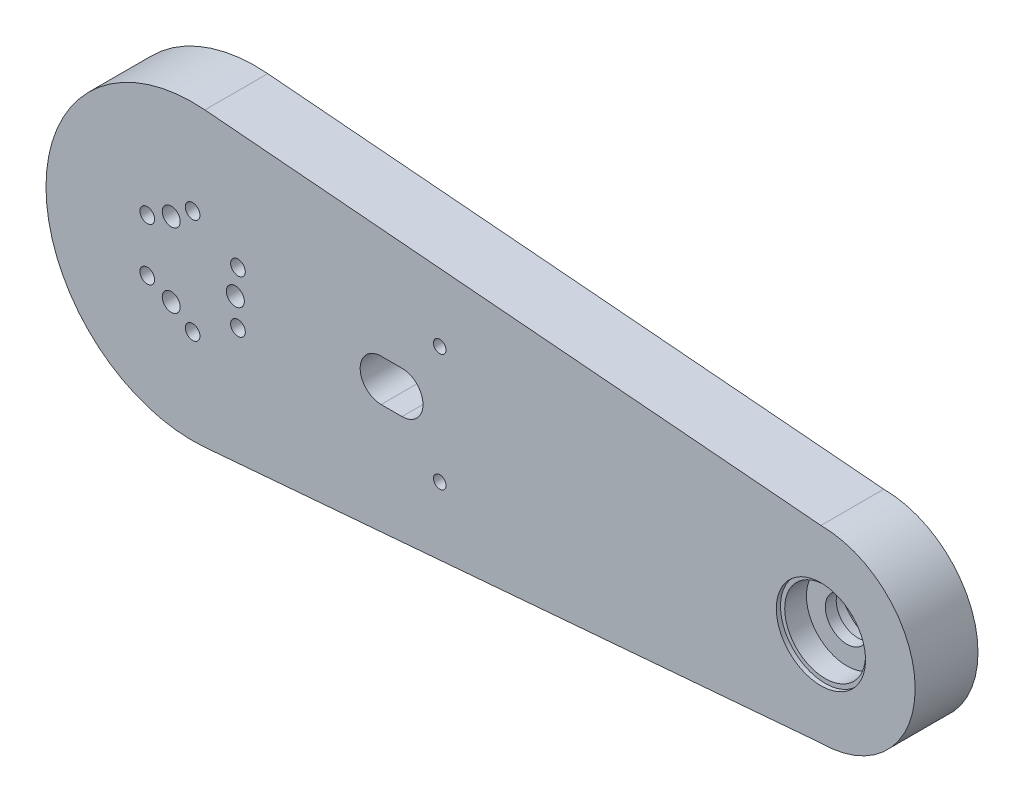
SolidWorks part; units mm, degrees
ref_plane "前视基准面" through (0, 0, 0) normal (0, 0, 1) x (1, 0, 0)
ref_plane "上视基准面" through (0, 0, 0) normal (0, 1, 0) x (1, 0, 0)
ref_plane "右视基准面" through (0, 0, 0) normal (1, 0, 0) x (0, 0, -1)
other "Configuration Table"
ref_plane "基准面2" through (0, 0, 15) normal (0, 0, 1) x (1, 0, 0)
sketch "草图2" plane through (0, 0, 15) normal (0, 0, 1) x (1, 0, 0)
  line L0 (150, 22.5) -> (2.9352, 34.8767)
  line L1 (2.9352, -34.8767) -> (150, -22.5)
  arc A0 (2.9352, 34.8767) -> (2.9352, -34.8767) centre (0, 0) ccw
  arc A1 (150, -22.5) -> (150, 22.5) centre (150, 0) ccw
  dimension "D1" = 35
  dimension "D2" = 22.5
  dimension "D3" = 147.0648
extrude "凸台-拉伸1" add sketch "草图2" against normal blind 15
sketch "草图3" plane through (0, 0, 0) normal (0, 0, -1) x (-1, 0, 0)
  line L0 (-45, 5) -> (-50, 5)
  line L1 (-50, -5) -> (-45, -5)
  arc A0 (-50, 5) -> (-50, -5) centre (-50, 0) ccw
  arc A1 (-45, -5) -> (-45, 5) centre (-45, 0) ccw
  dimension "D1" = 5
  dimension "D2" = 42.0648
  dimension "D3" = 47.0648
  dimension "D4" = 22.5
extrude "切除-拉伸1" cut sketch "草图3" against normal through all
ref_plane "基准面3" through (0, 0, 0) normal (0, -1, 0) x (1, 0, 0)
sketch "草图4" plane through (0, 0, 0) normal (0, -1, 0) x (1, 0, 0)
  line L0 (160.65, 15) -> (150, 15)
  line L1 (150, 15) -> (150, 0)
  line L2 (150, 0) -> (160.65, 0)
  line L3 (160.65, 0) -> (160.65, 1)
  line L4 (160.65, 1) -> (159.65, 1)
  line L5 (159.65, 1) -> (159.65, 6.2)
  line L6 (159.65, 6.2) -> (155.15, 6.2)
  line L7 (155.15, 6.2) -> (155.15, 8.8)
  line L8 (155.15, 8.8) -> (159.65, 8.8)
  line L9 (159.65, 8.8) -> (159.65, 14)
  line L10 (159.65, 14) -> (160.65, 14)
  line L11 (160.65, 14) -> (160.65, 15)
  line L12 (150, 15) -> (150, 0) construction
  dimension "D1" = 5.15
  dimension "D2" = 9.65
  dimension "D3" = 10.65
  dimension "D4" = 1
  dimension "D5" = 6.2
  dimension "D6" = 8.8
  dimension "D7" = 14
  dimension "D8" = 15
revolve "切除-旋转1" cut sketch "草图4" angle 360 about L12
hole_wizard "孔1" positions "草图6" profile "草图5" legacy
sketch "草图6" plane through (0, 0, 0) normal (0, 0, -1) x (-1, 0, 0)
  point P0 (5.1, 8.8335)
sketch "草图5" plane through (-5.1, 8.8335, 0) normal (1, 0, 0) x (0, 1, 0)
  line L0 (0, 0) -> (0, 15)
  line L1 (0, 15) -> (2.15, 15)
  line L2 (2.15, 15) -> (2.15, 0)
  line L3 (2.15, 0) -> (0, 0)
  line L4 (0, 110) -> (0, -10) construction
  dimension "直径" = 4.3
  dimension "深度" = 15
hole_wizard "孔2" positions "草图8" profile "草图7" legacy
sketch "草图8" plane through (0, 0, 0) normal (0, 0, -1) x (-1, 0, 0)
  point P0 (5.1, -8.8335)
sketch "草图7" plane through (-5.1, -8.8335, 0) normal (1, 0, 0) x (0, 1, 0)
  line L0 (0, 0) -> (0, 15)
  line L1 (0, 15) -> (2.15, 15)
  line L2 (2.15, 15) -> (2.15, 0)
  line L3 (2.15, 0) -> (0, 0)
  line L4 (0, 110) -> (0, -10) construction
  dimension "直径" = 4.3
  dimension "深度" = 15
hole_wizard "孔3" positions "草图10" profile "草图9" legacy
sketch "草图10" plane through (0, 0, 0) normal (0, 0, -1) x (-1, 0, 0)
  point P0 (-10.2, 0)
sketch "草图9" plane through (10.2, 0, 0) normal (1, 0, 0) x (0, 1, 0)
  line L0 (0, 0) -> (0, 15)
  line L1 (0, 15) -> (2.15, 15)
  line L2 (2.15, 15) -> (2.15, 0)
  line L3 (2.15, 0) -> (0, 0)
  line L4 (0, 110) -> (0, -10) construction
  dimension "直径" = 4.3
  dimension "深度" = 15
hole_wizard "孔4" positions "草图12" profile "草图11" legacy
sketch "草图12" plane through (0, 0, 0) normal (0, 0, -1) x (-1, 0, 0)
  point P0 (10.8253, 6.25)
sketch "草图11" plane through (-10.8253, 6.25, 0) normal (1, 0, 0) x (0, 1, 0)
  line L0 (0, 0) -> (0, 15)
  line L1 (0, 15) -> (1.75, 15)
  line L2 (1.75, 15) -> (1.75, 1)
  line L3 (1.75, 1) -> (3.25, 1)
  line L4 (3.25, 1) -> (3.25, 0)
  line L5 (3.25, 0) -> (0, 0)
  line L6 (0, 110) -> (0, -10) construction
  dimension "直径" = 3.5
  dimension "深度" = 15
  dimension "柱坑直径" = 6.5
  dimension "柱坑深度" = 1
hole_wizard "孔5" positions "草图14" profile "草图13" legacy
sketch "草图14" plane through (0, 0, 0) normal (0, 0, -1) x (-1, 0, 0)
  point P0 (0, 12.5)
sketch "草图13" plane through (0, 12.5, 0) normal (1, 0, 0) x (0, 1, 0)
  line L0 (0, 0) -> (0, 15)
  line L1 (0, 15) -> (1.75, 15)
  line L2 (1.75, 15) -> (1.75, 1)
  line L3 (1.75, 1) -> (3.25, 1)
  line L4 (3.25, 1) -> (3.25, 0)
  line L5 (3.25, 0) -> (0, 0)
  line L6 (0, 110) -> (0, -10) construction
  dimension "直径" = 3.5
  dimension "深度" = 15
  dimension "柱坑直径" = 6.5
  dimension "柱坑深度" = 1
hole_wizard "孔6" positions "草图16" profile "草图15" legacy
sketch "草图16" plane through (0, 0, 0) normal (0, 0, -1) x (-1, 0, 0)
  point P0 (-10.8253, 6.25)
sketch "草图15" plane through (10.8253, 6.25, 0) normal (1, 0, 0) x (0, 1, 0)
  line L0 (0, 0) -> (0, 15)
  line L1 (0, 15) -> (1.75, 15)
  line L2 (1.75, 15) -> (1.75, 1)
  line L3 (1.75, 1) -> (3.25, 1)
  line L4 (3.25, 1) -> (3.25, 0)
  line L5 (3.25, 0) -> (0, 0)
  line L6 (0, 110) -> (0, -10) construction
  dimension "直径" = 3.5
  dimension "深度" = 15
  dimension "柱坑直径" = 6.5
  dimension "柱坑深度" = 1
hole_wizard "孔7" positions "草图18" profile "草图17" legacy
sketch "草图18" plane through (0, 0, 0) normal (0, 0, -1) x (-1, 0, 0)
  point P0 (-10.8253, -6.25)
sketch "草图17" plane through (10.8253, -6.25, 0) normal (1, 0, 0) x (0, 1, 0)
  line L0 (0, 0) -> (0, 15)
  line L1 (0, 15) -> (1.75, 15)
  line L2 (1.75, 15) -> (1.75, 1)
  line L3 (1.75, 1) -> (3.25, 1)
  line L4 (3.25, 1) -> (3.25, 0)
  line L5 (3.25, 0) -> (0, 0)
  line L6 (0, 110) -> (0, -10) construction
  dimension "直径" = 3.5
  dimension "深度" = 15
  dimension "柱坑直径" = 6.5
  dimension "柱坑深度" = 1
hole_wizard "孔8" positions "草图20" profile "草图19" legacy
sketch "草图20" plane through (0, 0, 0) normal (0, 0, -1) x (-1, 0, 0)
  point P0 (0, -12.5)
sketch "草图19" plane through (0, -12.5, 0) normal (1, 0, 0) x (0, 1, 0)
  line L0 (0, 0) -> (0, 15)
  line L1 (0, 15) -> (1.75, 15)
  line L2 (1.75, 15) -> (1.75, 1)
  line L3 (1.75, 1) -> (3.25, 1)
  line L4 (3.25, 1) -> (3.25, 0)
  line L5 (3.25, 0) -> (0, 0)
  line L6 (0, 110) -> (0, -10) construction
  dimension "直径" = 3.5
  dimension "深度" = 15
  dimension "柱坑直径" = 6.5
  dimension "柱坑深度" = 1
hole_wizard "孔9" positions "草图22" profile "草图21" legacy
sketch "草图22" plane through (0, 0, 0) normal (0, 0, -1) x (-1, 0, 0)
  point P0 (10.8253, -6.25)
sketch "草图21" plane through (-10.8253, -6.25, 0) normal (1, 0, 0) x (0, 1, 0)
  line L0 (0, 0) -> (0, 15)
  line L1 (0, 15) -> (1.75, 15)
  line L2 (1.75, 15) -> (1.75, 1)
  line L3 (1.75, 1) -> (3.25, 1)
  line L4 (3.25, 1) -> (3.25, 0)
  line L5 (3.25, 0) -> (0, 0)
  line L6 (0, 110) -> (0, -10) construction
  dimension "直径" = 3.5
  dimension "深度" = 15
  dimension "柱坑直径" = 6.5
  dimension "柱坑深度" = 1
hole_wizard "孔10" positions "草图24" profile "草图23" legacy
sketch "草图24" plane through (0, 0, 0) normal (0, 0, -1) x (-1, 0, 0)
  point P0 (-59, -14)
sketch "草图23" plane through (59, -14, 0) normal (1, 0, 0) x (0, 1, 0)
  line L0 (0, 0) -> (0, 15)
  line L1 (0, 15) -> (1.5, 15)
  line L2 (1.5, 15) -> (1.5, 0)
  line L3 (1.5, 0) -> (0, 0)
  line L4 (0, 110) -> (0, -10) construction
  dimension "直径" = 3
  dimension "深度" = 15
hole_wizard "孔11" positions "草图26" profile "草图25" legacy
sketch "草图26" plane through (0, 0, 0) normal (0, 0, -1) x (-1, 0, 0)
  point P0 (-59, 14)
sketch "草图25" plane through (59, 14, 0) normal (1, 0, 0) x (0, 1, 0)
  line L0 (0, 0) -> (0, 15)
  line L1 (0, 15) -> (1.5, 15)
  line L2 (1.5, 15) -> (1.5, 0)
  line L3 (1.5, 0) -> (0, 0)
  line L4 (0, 110) -> (0, -10) construction
  dimension "直径" = 3
  dimension "深度" = 15
